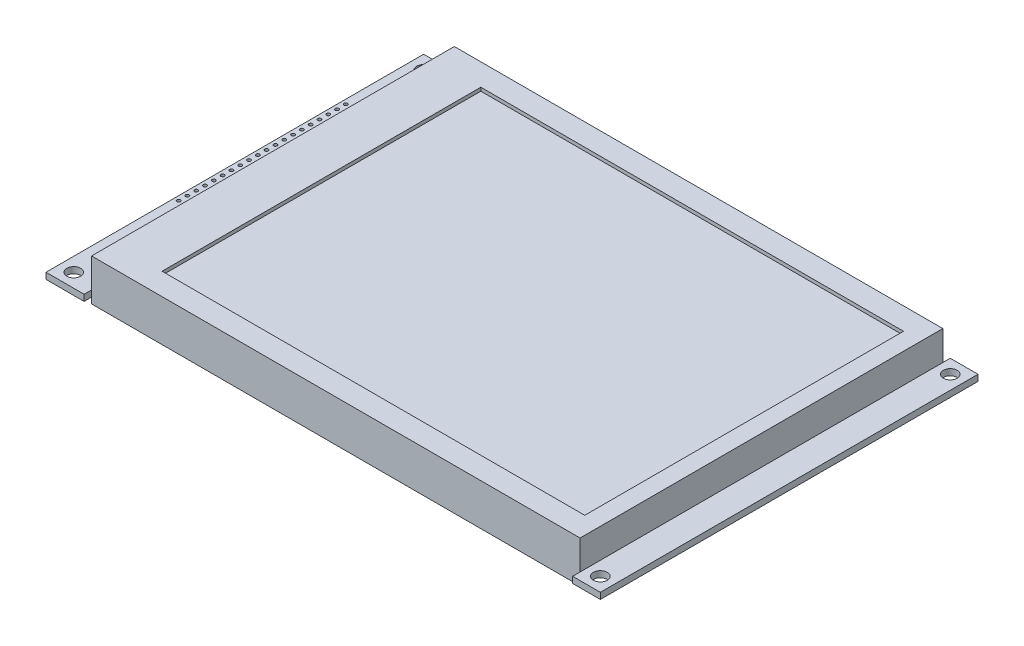
SolidWorks part; units mm, degrees
ref_plane "前视基准面" through (0, 0, 0) normal (0, 0, 1) x (1, 0, 0)
ref_plane "上视基准面" through (0, 0, 0) normal (0, 1, 0) x (1, 0, 0)
ref_plane "右视基准面" through (0, 0, 0) normal (1, 0, 0) x (0, 0, -1)
sketch "草图1" plane through (0, 0, 0) normal (0, 1, 0) x (1, 0, 0)
  line L0 (-63.9633, 0) -> (67.3002, 0) construction
  line L1 (0, 0) -> (0, 107.1606) construction
  line L2 (0, 107.1606) -> (0, -96.3101) construction
  line L3 (-80, 54.5) -> (80, 54.5)
  line L4 (80, 54.5) -> (80, -54.5)
  line L5 (80, -54.5) -> (-80, -54.5)
  line L6 (-80, -54.5) -> (-80, 54.5)
  dimension "D1" = 160
  dimension "D2" = 109
extrude "拉伸1" add sketch "草图1" along normal blind 1.8
sketch "草图2" plane through (0, 1.8, 0) normal (0, 1, 0) x (-1, 0, 0)
  line L0 (-61.3137, 0) -> (62.2839, 0) construction
  line L1 (0, -90.6123) -> (0, 87.3138) construction
  circle A0 centre (-76, -50.5) radius 2
  circle A1 centre (-76, 50.5) radius 2
  circle A2 centre (76, 50.5) radius 2
  circle A3 centre (76, -50.5) radius 2
  dimension "D1" = 101
  dimension "D3" = 4
  dimension "D2" = 152
extrude "切除-拉伸1" cut sketch "草图2" against normal through all
sketch "草图3" plane through (0, 1.8, 0) normal (0, 1, 0) x (-1, 0, 0)
  line L0 (96.4333, 0) -> (-89.0601, 0) construction
  line L1 (69, -54.5) -> (69, -52.35)
  line L3 (69, -52.35) -> (-72, -52.35)
  line L4 (-72, -54.5) -> (-72, -52.35)
  line L5 (69, 54.5) -> (69, 52.35)
  line L6 (80, 54.5) -> (-80, 54.5) construction
  line L7 (69, 52.35) -> (-72, 52.35)
  line L8 (-72, 52.35) -> (-72, 54.5)
  line L9 (80, -54.5) -> (80, 54.5) construction
  line L10 (69, -54.5) -> (-72, -54.5)
  line L11 (-80, -54.5) -> (80, -54.5) construction
  line L12 (69, 54.5) -> (-72, 54.5)
  dimension "D1" = 104.7
  dimension "D2" = 11
  dimension "D3" = 141
extrude "切除-拉伸3" cut sketch "草图3" against normal through all
sketch "草图4" plane through (0, 1.8, 0) normal (0, 1, 0) x (-1, 0, 0)
  line L0 (69, -54.5) -> (69, -52.35) construction
  line L1 (85.7616, 0) -> (-88.0899, 0) construction
  line L3 (69, -52.35) -> (-72, -52.35)
  line L4 (69, -52.35) -> (69, 52.35)
  line L5 (69, 52.35) -> (-72, 52.35)
  line L6 (-72, -52.35) -> (-72, 52.35)
  dimension "D1" = 141
  dimension "D2" = 104.7
extrude "拉伸2" add sketch "草图4" along normal blind 8.5
sketch "草图5" plane through (0, 10.3, 0) normal (0, 1, 0) x (-1, 0, 0)
  line L0 (84.5974, 0) -> (-85.9556, 0) construction
  line L1 (69, -52.35) -> (69, 52.35) construction
  line L2 (55, -46) -> (-67, -46)
  line L3 (55, -46) -> (55, 46)
  line L4 (55, 46) -> (-67, 46)
  line L5 (-67, -46) -> (-67, 46)
  dimension "D1" = 122
  dimension "D2" = 92
  dimension "D3" = 14
extrude "切除-拉伸4" cut sketch "草图5" against normal blind 1
sketch "草图6" plane through (0, 1.8, 0) normal (0, 1, 0) x (-1, 0, 0)
  line L0 (78.72, -68.9401) -> (78.72, 90.026) construction
  line L1 (80, -54.5) -> (80, 54.5) construction
  line L2 (80, 54.5) -> (69, 54.5) construction
  circle A0 centre (78.72, 17.5) radius 0.5
  circle A1 centre (78.72, 14.96) radius 0.5
  circle A2 centre (78.72, 12.42) radius 0.5
  circle A3 centre (78.72, 9.88) radius 0.5
  circle A4 centre (78.72, 7.34) radius 0.5
  circle A5 centre (78.72, 4.8) radius 0.5
  circle A6 centre (78.72, 2.26) radius 0.5
  circle A7 centre (78.72, -0.28) radius 0.5
  circle A8 centre (78.72, -2.82) radius 0.5
  circle A9 centre (78.72, -5.36) radius 0.5
  circle A10 centre (78.72, -7.9) radius 0.5
  circle A11 centre (78.72, -10.44) radius 0.5
  circle A12 centre (78.72, -12.98) radius 0.5
  circle A13 centre (78.72, -15.52) radius 0.5
  circle A14 centre (78.72, -18.06) radius 0.5
  circle A15 centre (78.72, -20.6) radius 0.5
  circle A16 centre (78.72, -23.14) radius 0.5
  circle A17 centre (78.72, -25.68) radius 0.5
  circle A18 centre (78.72, -28.22) radius 0.5
  circle A19 centre (78.72, -30.76) radius 0.5
  dimension "D2" = 1
  dimension "D1" = 1.28
  dimension "D3" = 37
extrude "切除-拉伸5" cut sketch "草图6" against normal through all
sketch "草图7" plane through (0, 0, 0) normal (0, -1, 0) x (1, 0, 0)
  line L1 (72, 52.35) -> (-69, 52.35)
  line L2 (72, 52.35) -> (72, -52.35)
  line L3 (72, -52.35) -> (-69, -52.35)
  line L4 (-69, 52.35) -> (-69, -52.35)
extrude "拉伸3" add sketch "草图7" along normal offset from surface (1.7 mm away) 12 up to face at (6, 10.3, 0)
sketch "草图8" plane through (0, 1.8, 0) normal (0, 1, 0) x (-1, 0, 0)
  line L0 (79.5594, 17.5) -> (77.8443, 17.5) construction
  line L1 (78.72, 16.8284) -> (78.72, 18.3007) construction
